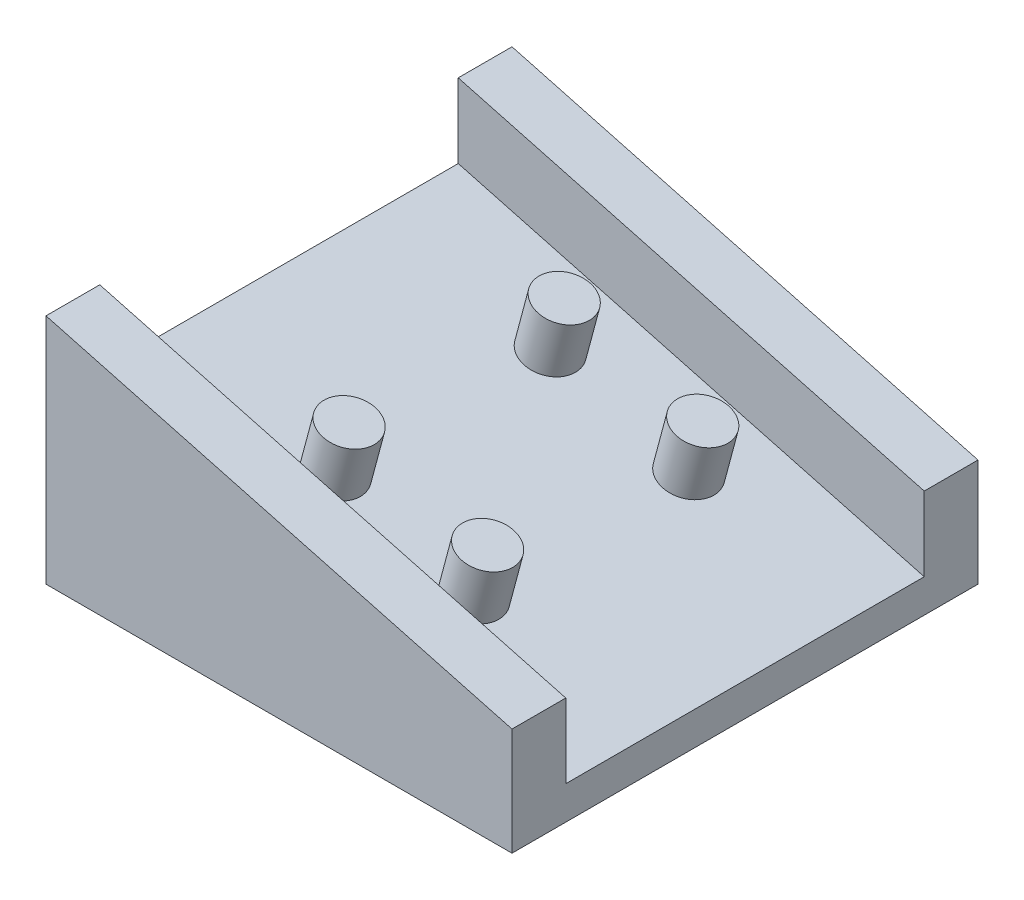
SolidWorks part; units mm, degrees
ref_plane "Front Plane" through (0, 0, 0) normal (0, 0, 1) x (1, 0, 0)
ref_plane "Top Plane" through (0, 0, 0) normal (0, 1, 0) x (1, 0, 0)
ref_plane "Right Plane" through (0, 0, 0) normal (1, 0, 0) x (0, 0, -1)
sketch "Sketch1" plane through (0, 0, 0) normal (0, 1, 0) x (1, 0, 0)
  line L0 (13, 26) -> (13, 0) construction
  line L1 (0, 0) -> (26, 0)
  line L2 (0, 0) -> (0, 26)
  line L3 (0, 26) -> (26, 26)
  line L4 (26, 0) -> (26, 26)
  line L5 (0, 13) -> (26, 13) construction
  point P9 (13, 13)
  dimension "D1" = 26
extrude "Boss-Extrude1" add sketch "Sketch1" along normal blind 12.9667
sketch "Sketch2" plane through (0, 0, 0) normal (0, 0, 1) x (1, 0, 0)
  line L0 (0, 12.9667) -> (26, 6)
  line L1 (0, 12.9667) -> (26, 12.9667) construction
  line L2 (26, 12.9667) -> (26, 0) construction
  line L3 (0, 12.9667) -> (26, 12.9667)
  line L4 (26, 12.9667) -> (26, 6)
  dimension "D2" = 6
  dimension "D3" = 15
extrude "Cut-Extrude1" cut sketch "Sketch2" against normal through all
sketch "Sketch3" plane through (3.2417, 12.0981, 0) normal (0.2588, 0.9659, 0) x (0.9659, -0.2588, 0)
  line L0 (-3.356, 26) -> (-3.356, 0) construction
  line L1 (-3.356, 3) -> (46.644, 3)
  line L2 (-3.356, 3) -> (-3.356, 23)
  line L3 (-3.356, 23) -> (46.644, 23)
  line L4 (46.644, 3) -> (46.644, 23)
  point P6 (29.8974, 25)
  point P7 (35.5506, 5)
  point P8 (26.8227, -11.5317)
  point P9 (-3.356, 13)
  point P10 (-3.356, 13)
  point P11 (0, 0)
  point P12 (0, 0)
  dimension "D1" = 20
  dimension "D2" = 50
extrude "Cut-Extrude2" cut sketch "Sketch3" against normal blind 4
sketch "Sketch5" plane through (2.2064, 8.2344, 0) normal (0.2588, 0.9659, 0) x (0.9659, -0.2588, 0)
  line L0 (-2.2842, 13) -> (24.633, 13) construction
  line L1 (-2.2842, 3) -> (-2.2842, 23) construction
  line L2 (24.633, 23) -> (24.633, 3) construction
  line L3 (11.1744, 23) -> (11.1744, 3) construction
  line L4 (24.633, 23) -> (-2.2842, 23) construction
  line L5 (-2.2842, 3) -> (24.633, 3) construction
  circle A0 centre (7.1744, 19) radius 1.45
  circle A1 centre (7.1744, 7) radius 1.45
  circle A2 centre (15.1744, 19) radius 1.45
  circle A3 centre (15.1744, 7) radius 1.45
  point P14 (0, 0)
  point P17 (7.696, 25)
  dimension "D1" = 2.9
  dimension "D2" = 4
  dimension "D3" = 4
extrude "Boss-Extrude2" add sketch "Sketch5" along normal blind 3
equation "\"TrackLength\"= 150"
equation "\"MarbleWidth\"= 13"
equation "\"MarbleTrackWidth\"= \"MarbleWidth\" - 1"
equation "\"TrackWidth\"= \"MarbleTrackWidth\" + ( 2 * 4 )"
equation "\"MarbleTrackLength\"= \"TrackLength\" - ( 2 * 8 )"
equation "\"MountWidth\" = \"TrackWidth\" + 6"
equation "\"D1@Sketch1\"=\"MountWidth\""
equation "\"D1@Boss-Extrude1\"=\"RampHeight\""
equation "\"RampDepth\"=6"
equation "\"D2@Sketch2\"=\"RampDepth\""
equation "\"RampAngle\"= 15"
equation "\"RampHeight\"= ( \"MountWidth\" * tan ( \"RampAngle\" ) ) + \"RampDepth\""
equation "\"D1@Sketch3\"=\"TrackWidth\""
equation "\"MountWidth\"= \"TrackWidth\" + 10"
equation "\"MountLength\"=66.6651"
